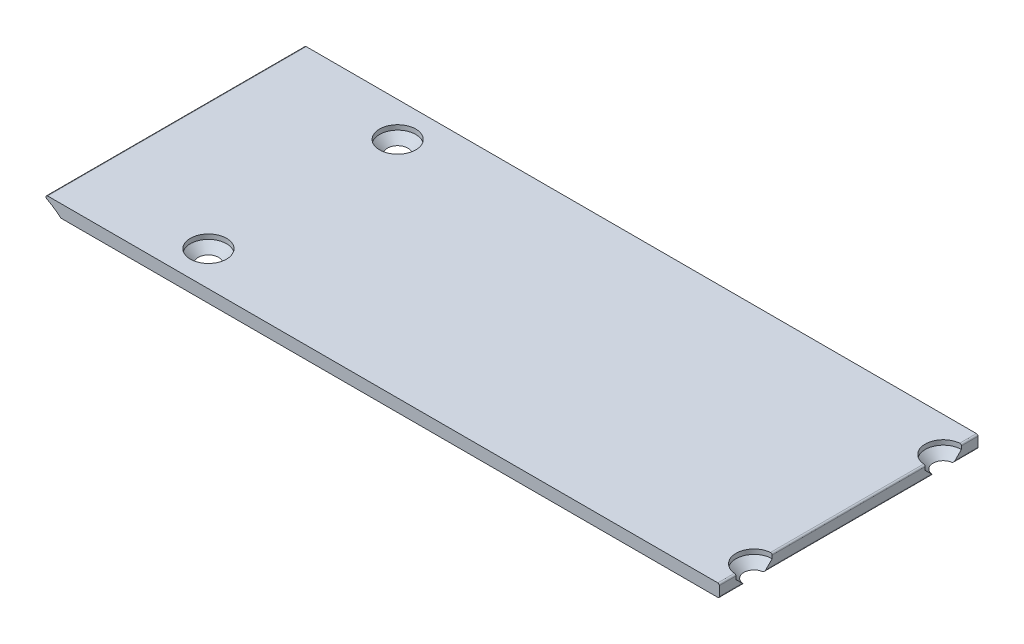
SolidWorks part; units mm, degrees
ref_plane "Ebene vorne" through (0, 0, 0) normal (0, 0, 1) x (1, 0, 0)
ref_plane "Ebene oben" through (0, 0, 0) normal (0, 1, 0) x (1, 0, 0)
ref_plane "Ebene rechts" through (0, 0, 0) normal (1, 0, 0) x (0, 0, -1)
sketch "Skizze2" plane through (0, 0, 0) normal (0, 0, 1) x (1, 0, 0)
  line L12 (0, 23) -> (435, 23) construction
  line L14 (9.798, 23) -> (225, 23)
  line L16 (225, 25) -> (225, 19) construction
  line L17 (225, 19) -> (17.0074, 19) construction
  line L18 (225, 23) -> (225, 19)
  line L19 (225, 19) -> (17.0074, 19)
  line L20 (15.4677, 19) -> (17.0074, 19) construction
  line L21 (16.2481, 19) -> (17.0074, 19)
  circle A2 centre (0, 0) radius 25 construction
  arc A3 (16.2481, 19) -> (9.798, 23) centre (0, 0) ccw
extrude "Aufsatz-Linear austragen1" add sketch "Skizze2" against normal up to vertex (49.5 mm away) from vertex at -8.5
fillet "Verrundung1" radius 0.5 4 edges at (225, 19, -29) (225, 23, -29) (16.2481, 19, -29) (9.798, 23, -29)
ref_plane "Ebene1" through (52, 0, 0) normal (1, 0, 0) x (0, 0, -1)
sketch "Skizze3" plane through (52, 0, 0) normal (1, 0, 0) x (0, 0, -1)
  point P0 (19.5, 25)
sketch "Skizze4" plane through (225, 0, 0) normal (1, 0, 0) x (0, 0, -1)
  point P0 (19.5, 25)
sketch "Skizze5" plane through (0, 23, 0) normal (0, 1, 0) x (1, 0, 0)
  point P0 (225, 19.5)
  point P2 (52, 19.5)
hole_wizard "Formsenkung für M5 Senkschraube mit Innensechskant1" positions "Skizze5" profile "Skizze6" countersink size "M5" standard "DIN"
sketch "Skizze6" plane through (225, 23, -19.5) normal (1, 0, 0) x (0, 0, 1)
  line L0 (0, 0) -> (0, 5.6524)
  line L1 (0, 5.6524) -> (2.75, 4)
  line L2 (2.75, 4) -> (2.75, 4.485)
  line L3 (2.75, 4.485) -> (5.735, 1.5)
  line L4 (5.735, 1.5) -> (5.735, 0)
  line L6 (5.735, 0) -> (0, 0)
  line L7 (-2.75, 4.485) -> (-5.735, 1.5) construction
  line L10 (0, 5.6524) -> (-2.75, 4) construction
  line L11 (0, -6.35) -> (0, 107.95) construction
  dimension "Bohrerdurchmesser" = 5.5
  dimension "Bohrungstiefe" = 4
  dimension "Senkdurchmesser2" = 11.47
  dimension "Senkwinkel2" = 90
  dimension "Spitzenwinkel" = 118
  dimension "Kopfspielraum" = 1.5
mirror "Spiegeln2" about plane through (0, 0, -49.5) normal (0, 0, 1) of bodies 105 102
